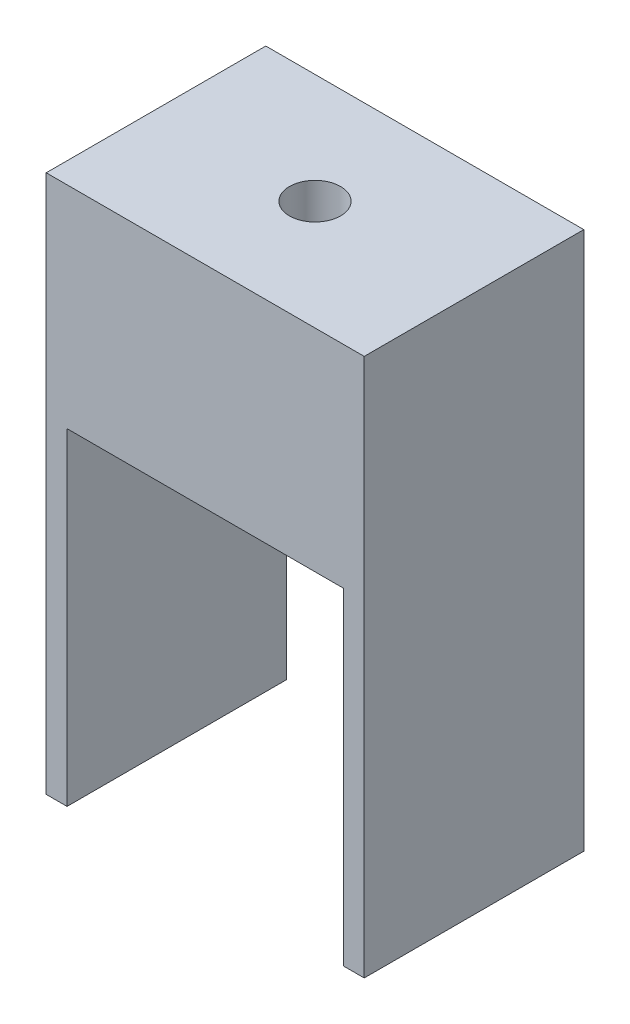
SolidWorks part; units mm, degrees
ref_plane "Front Plane" through (0, 0, 0) normal (0, 0, 1) x (1, 0, 0)
ref_plane "Top Plane" through (0, 0, 0) normal (0, 1, 0) x (1, 0, 0)
ref_plane "Right Plane" through (0, 0, 0) normal (1, 0, 0) x (0, 0, -1)
sketch "Sketch1" plane through (0, 0, 0) normal (0, 1, 0) x (1, 0, 0)
  line L1 (-22.89, 15.805) -> (22.89, 15.805)
  line L2 (-22.89, 15.805) -> (-22.89, -15.805)
  line L3 (-22.89, -15.805) -> (22.89, -15.805)
  line L4 (22.89, 15.805) -> (22.89, -15.805)
  line L5 (-22.89, 15.805) -> (22.89, -15.805) construction
  line L6 (-22.89, -15.805) -> (22.89, 15.805) construction
  point P0 (0, 0)
  dimension "D1" = 0
  dimension "D2" = 0
  dimension "D3" = 45.78
  dimension "D4" = 31.61
extrude "Boss-Extrude2" add sketch "Sketch1" along normal blind 77.5
sketch "Sketch2" plane through (0, 77.5, 0) normal (0, 1, 0) x (1, 0, 0)
  circle A0 centre (0, 0) radius 3.675
  point P2 (0, -0.0015)
  point P4 (0, -0.0015)
  point P5 (0, -0.0015)
  point P6 (0, -0.0015)
  point P7 (0, 0)
  dimension "D2" = 7.35
  dimension "D1" = 0
extrude "Cut-Extrude1" cut sketch "Sketch2" against normal blind 25.4
sketch "Sketch3" plane through (0, 0, -15.805) normal (0, 0, -1) x (-1, 0, 0)
  line L0 (-22.89, 0) -> (22.89, 0) construction
  line L1 (19.89, 0) -> (-19.89, 0)
  line L2 (19.89, 0) -> (19.89, 47.1)
  line L3 (19.89, 47.1) -> (-19.89, 47.1)
  line L4 (-19.89, 0) -> (-19.89, 47.1)
  line L5 (22.89, 77.5) -> (22.89, 0) construction
  line L6 (-22.89, 77.5) -> (-22.89, 0) construction
  point P10 (0, 47.1)
  dimension "D1" = 3
  dimension "D2" = 3
  dimension "D3" = 47.1
extrude "Cut-Extrude3" cut sketch "Sketch3" against normal through all contours L3 L4 L1 L2
